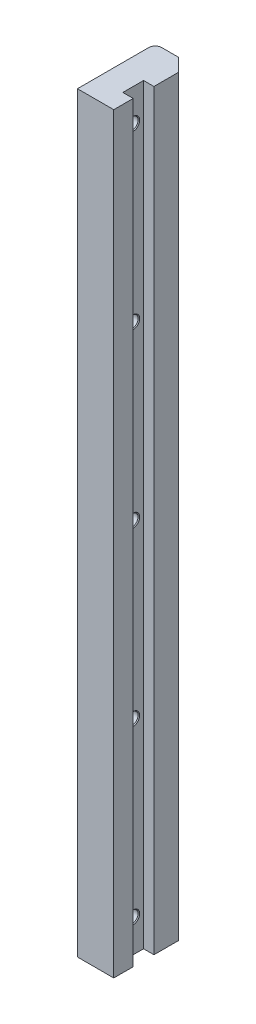
SolidWorks part; units mm, degrees
ref_plane "Front Plane" through (0, 0, 0) normal (1, 0, 0) x (0, 1, 0)
ref_plane "Top Plane" through (0, 0, 0) normal (0, 0, 1) x (0, 1, 0)
ref_plane "Right Plane" through (0, 0, 0) normal (0, 1, 0) x (-1, 0, 0)
sketch "Sketch2" plane through (0, 0, 0) normal (0, 1, 0) x (-1, 0, 0)
  line L1 (-14, -30) -> (14, -30)
  line L2 (-14, -30) -> (-14, 30)
  line L3 (-14, 30) -> (14, 30)
  line L4 (14, -30) -> (14, 30)
  line L5 (-14, -30) -> (14, 30) construction
  line L6 (-14, 30) -> (14, -30) construction
  point P0 (0, 0)
  dimension "D1" = 60
  dimension "D2" = 28
extrude "Boss-Extrude1" add sketch "Sketch2" along normal mid plane 580
sketch "Sketch3" plane through (0, 290, 0) normal (0, 1, 0) x (-1, 0, 0)
  line L0 (-14, 30) -> (-14, -30) construction
  line L1 (-14, 15) -> (-6, 15)
  line L2 (-14, 15) -> (-14, -1)
  line L3 (-14, -1) -> (-6, -1)
  line L4 (-6, 15) -> (-6, -1)
  line L5 (14, 30) -> (-14, 30) construction
  dimension "D1" = 15
  dimension "D2" = 16
  dimension "D3" = 8
extrude "Cut-Extrude1" cut sketch "Sketch3" against normal through all
chamfer "Chamfer1" distance 10 angle 45 1 edges at (14, 0, -30)
fillet "Fillet1" radius 5 1 edges at (-14, 0, -30)
sketch "Sketch4" plane through (6, 0, 0) normal (1, 0, 0) x (0, 1, 0)
  line L0 (-290, -1) -> (-290, 15) construction
  line L3 (290, 30) -> (-290, 30) construction
  point P0 (-265, 7)
  dimension "D1" = 25
  dimension "D2" = 23
hole_wizard "M10x1.25 Tapped Hole1" positions "Sketch4" profile "Sketch5" tap size "M10x1.25" standard "ISO" end condition through all
sketch "Sketch5" plane through (6, -265, 7) normal (0, 1, 0) x (0, 0, -1)
  line L0 (0, 0) -> (0, 20)
  line L1 (0, 20) -> (4.4, 20)
  line L2 (4.4, 20) -> (4.4, 0.625)
  line L3 (4.4, 0.625) -> (5.025, 0)
  line L5 (5.025, 0) -> (0, 0)
  line L6 (-4.4, 0.625) -> (-5.025, 0) construction
  line L11 (0, -6.35) -> (0, 107.95) construction
  dimension "Thru Tap Drill Dia." = 8.8
  dimension "Thru Tap Drill Depth" = 20
  dimension "Near C'Sink Dia." = 10.05
  dimension "Near C'Sink Angle" = 90
cosmetic thread "Hole Thread1" parameters "D2"=10
pattern_linear "LPattern1" count 5 spacing 132.5 along (0, 1, 0) of "M10x1.25 Tapped Hole1"
cosmetic thread "Hole Thread2" parameters "D2"=10
cosmetic thread "Hole Thread3" parameters "D2"=10
cosmetic thread "Hole Thread4" parameters "D2"=10
cosmetic thread "Hole Thread5" parameters "D2"=10
